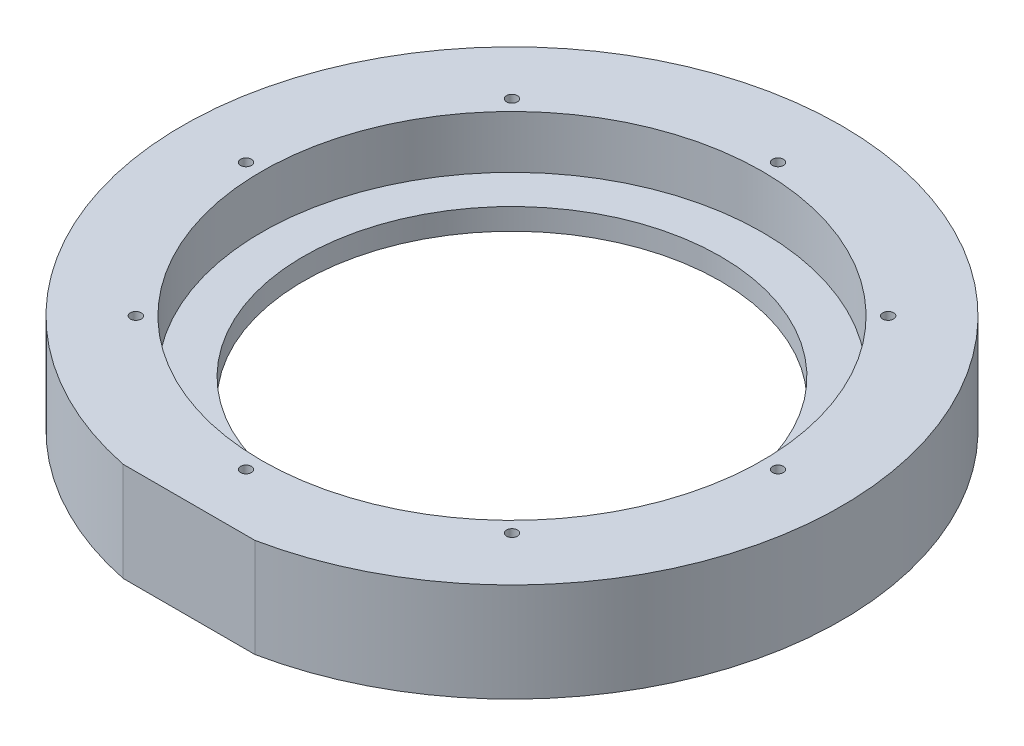
SolidWorks part; units mm, degrees
material "AISI 304"
ref_plane "Front" through (0, 0, 0) normal (0, 0, 1) x (1, 0, 0)
ref_plane "Top" through (0, 0, 0) normal (0, 1, 0) x (1, 0, 0)
ref_plane "Right" through (0, 0, 0) normal (1, 0, 0) x (0, 0, -1)
sketch "Sketch1" plane through (0, 0, 0) normal (0, 0, 1) x (1, 0, 0)
  line L0 (0, 0) -> (0, 28.575) construction
  line L2 (80.3783, 0) -> (99.4283, 0)
  line L3 (127, -9.525) -> (127, 28.575)
  line L4 (127, 28.575) -> (96.5, 28.575)
  line L8 (80.3783, 8.255) -> (80.3783, 0)
  line L9 (80.3783, 8.255) -> (96.5, 8.255)
  line L10 (96.5, 8.255) -> (96.5, 28.575)
  line L11 (99.4283, 0) -> (99.4283, -6.985)
  line L12 (99.4283, -6.985) -> (109.7915, -6.985)
  line L13 (109.7915, -6.985) -> (109.7915, -9.525)
  line L14 (109.7915, -9.525) -> (127, -9.525)
  point P14 (127, -8.9459)
  dimension "D1" = 160.7566
  dimension "D2" = 254
  dimension "D3" = 20.32
  dimension "D4" = 38.1
  dimension "D5" = 193
  dimension "D6" = 219.583
  dimension "D7" = 19.05
  dimension "D8" = 2.54
  dimension "D9" = 6.985
revolve "Revolve1" add sketch "Sketch1" angle 360 about L0
hole_wizard "M5x0.8 Tapped Hole1" positions "Sketch2" profile "Sketch3" tap size "M5x0.8" standard "ANSI Metric"
sketch "Sketch2" plane through (0, 28.575, 0) normal (0, 1, 0) x (1, 0, 0)
  line L0 (0, 0) -> (0, 102.5) construction
  point P0 (0, 102.5)
  point P6 (72.4784, 72.4784)
  point P7 (102.5, 0)
  point P8 (72.4784, -72.4784)
  point P9 (0, -102.5)
  point P10 (-72.4784, -72.4784)
  point P11 (-102.5, 0)
  point P12 (-72.4784, 72.4784)
  dimension "D2" = 102.5
  dimension "D1" = 8
sketch "Sketch3" plane through (0, 28.575, -102.5) normal (1, 0, 0) x (0, 0, 1)
  line L0 (0, 0) -> (0, 18.6608)
  line L1 (0, 18.6608) -> (2.1, 17.399)
  line L2 (2.1, 17.399) -> (2.1, 0)
  line L5 (2.1, 0) -> (0, 0)
  line L10 (0, 18.6608) -> (-2.1, 17.399) construction
  line L11 (0, -6.35) -> (0, 107.95) construction
  dimension "Tap Drill Dia." = 4.2
  dimension "Tap Drill Depth" = 17.399
  dimension "Drill Angle" = 118
cosmetic thread "Hole Thread2" parameters "D1"=15, "D2"=5
cosmetic thread "Hole Thread3" parameters "D1"=15, "D2"=5
cosmetic thread "Hole Thread4" parameters "D1"=15, "D2"=5
cosmetic thread "Hole Thread5" parameters "D1"=15, "D2"=5
cosmetic thread "Hole Thread6" parameters "D1"=15, "D2"=5
cosmetic thread "Hole Thread7" parameters "D1"=15, "D2"=5
cosmetic thread "Hole Thread8" parameters "D1"=15, "D2"=5
cosmetic thread "Hole Thread9" parameters "D1"=15, "D2"=5
sketch "Sketch7" plane through (0, 28.575, 0) normal (0, 1, 0) x (1, 0, 0)
  line L1 (-25.4, -124.4341) -> (25.4, -124.4341)
  line L2 (-25.4, -124.4341) -> (-25.4, -127)
  line L3 (-25.4, -127) -> (25.4, -127)
  line L4 (25.4, -124.4341) -> (25.4, -127)
  circle A0 centre (0, 0) radius 127 construction
  dimension "D1" = 50.8
extrude "Cut-Extrude1" cut sketch "Sketch7" against normal up to next
hole_wizard "#8-32 Tapped Hole1" positions "Sketch8" profile "Sketch10" tap size "#8-32" standard "ANSI Inch" end condition up to next
sketch "Sketch8" plane through (0, 0, 0) normal (0, -1, 0) x (-1, 0, 0)
  line L0 (-6.35, -85.09) -> (6.35, -85.09) construction
  line L2 (0, -85.09) -> (0, 0) construction
  point P0 (-6.35, -85.09)
  point P2 (6.35, -85.09)
  dimension "D1" = 85.09
  dimension "D2" = 12.7
sketch "Sketch10" plane through (6.35, 0, 85.09) normal (1, 0, 0) x (0, 0, -1)
  line L0 (0, 0) -> (0, 8.255)
  line L1 (0, 8.255) -> (1.7272, 8.255)
  line L2 (1.7272, 8.255) -> (1.7272, 0)
  line L5 (1.7272, 0) -> (0, 0)
  line L11 (0, -6.35) -> (0, 107.95) construction
  dimension "Thru Tap Drill Dia." = 3.4544
  dimension "Thru Tap Drill Depth" = 8.255
cosmetic thread "Hole Thread10" parameters "D2"=4.1656
cosmetic thread "Hole Thread11" parameters "D2"=4.1656
